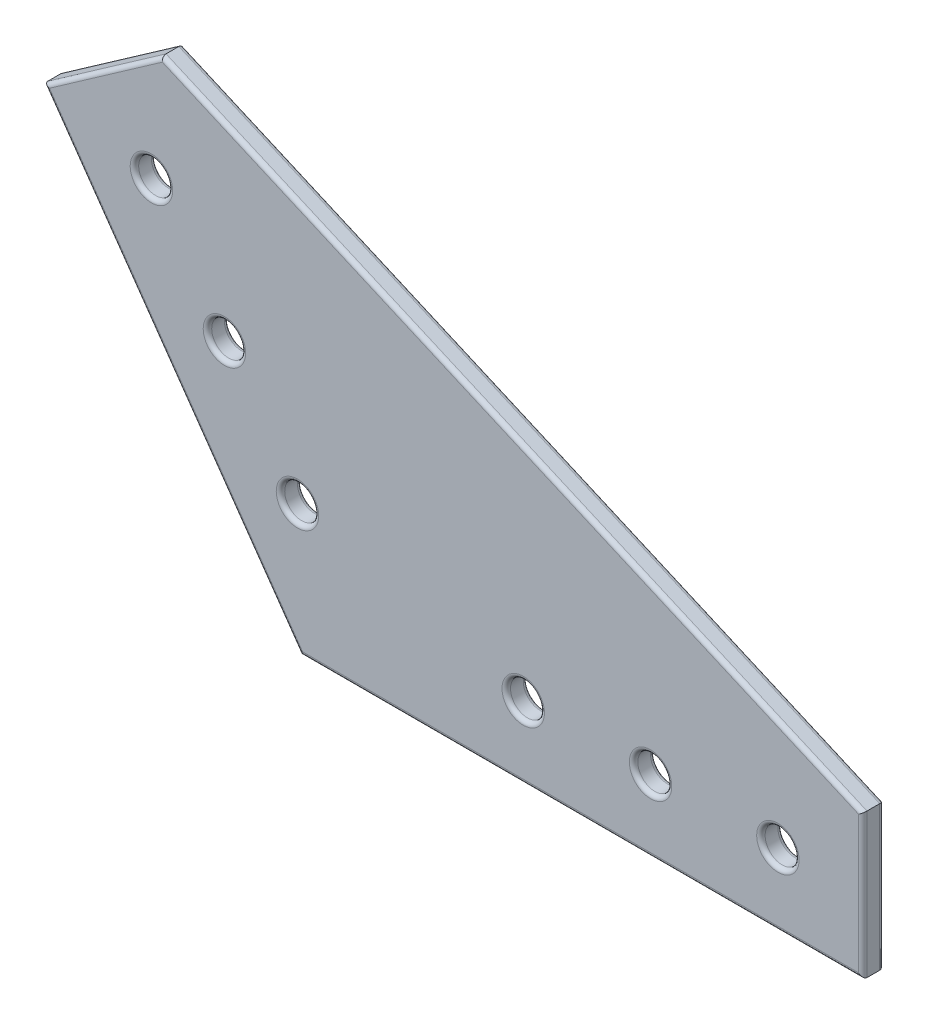
SolidWorks part; units mm, degrees
ref_plane "Front Plane" through (0, 0, 0) normal (0, 0, 1) x (1, 0, 0)
ref_plane "Top Plane" through (0, 0, 0) normal (0, 1, 0) x (1, 0, 0)
ref_plane "Right Plane" through (0, 0, 0) normal (1, 0, 0) x (0, 0, -1)
sketch "Sketch1" plane through (0, 0, 0) normal (0, 0, 1) x (1, 0, 0)
  line L0 (-141.463, 22.5991) -> (-113.6118, 42.1007)
  line L1 (-113.6118, 42.1007) -> (51.5493, -29.8214)
  line L2 (51.5493, -29.8214) -> (51.5493, -63.8214)
  line L3 (51.5493, -63.8214) -> (-80.9507, -63.8214)
  line L4 (-80.9507, -63.8214) -> (-141.463, 22.5991)
  dimension "D1" = 132.5
  dimension "D2" = 34
  dimension "D3" = 105.5
  dimension "D4" = 80.9507
  dimension "D5" = 63.8214
  dimension "D6" = 90
  dimension "D7" = 125
  dimension "D8" = 34
extrude "Boss-Extrude1" add sketch "Sketch1" along normal blind 5
sketch "Sketch2" plane through (0, 0, 5) normal (0, 0, 1) x (1, 0, 0)
  line L0 (-113.6118, 42.1007) -> (-39.4443, -63.8214) construction
  line L1 (-80.9507, -63.8214) -> (51.5493, -63.8214) construction
  line L2 (-141.463, 22.5991) -> (-80.9507, -63.8214) construction
  line L3 (51.5493, -29.8214) -> (-104.7577, -29.8214) construction
  line L4 (-127.5374, 32.3499) -> (-60.1975, -63.8214) construction
  line L5 (-113.6118, 42.1007) -> (-141.463, 22.5991) construction
  line L6 (51.5493, -46.8214) -> (-92.8542, -46.8214) construction
  line L7 (51.5493, -63.8214) -> (51.5493, -29.8214) construction
  line L8 (21.5493, -46.8214) -> (-122.8542, -46.8214) construction
  line L9 (-8.4507, -46.8214) -> (-152.8542, -46.8214) construction
  line L10 (-38.4507, -46.8214) -> (-182.8542, -46.8214) construction
  circle A0 centre (-116.0659, 15.9669) radius 4
  circle A1 centre (31.5493, -46.8214) radius 4
  circle A2 centre (-98.8586, -8.6077) radius 4
  circle A3 centre (-81.6513, -33.1822) radius 4
  circle A4 centre (1.5493, -46.8214) radius 4
  circle A5 centre (-28.4507, -46.8214) radius 4
  circle A7 centre (-58.4507, -46.8214) radius 4 [skipped]
  dimension "D1" = 8
  dimension "D2" = 8
  dimension "D4" = 20
  dimension "D5" = 30
  dimension "D7" = 20
  dimension "D8" = 30
  dimension "D3" = 3
  dimension "D6" = 4
extrude "Cut-Extrude1" cut sketch "Sketch2" against normal through all
fillet "Fillet2" radius 1 22 edges at (-127.5374, 32.3499, 0) (-111.2068, -20.6112, 0) (-14.7007, -63.8214, 0) (51.5493, -46.8214, 0) (-31.0312, 6.1396, 0) (5.5493, -46.8214, 0) (-77.6513, -33.1822, 0) (-94.8586, -8.6077, 0) (-112.0659, 15.9669, 0) (-24.4507, -46.8214, 0) (35.5493, -46.8214, 0) (-14.7007, -63.8214, 5) (-111.2068, -20.6112, 5) (-127.5374, 32.3499, 5) (-31.0312, 6.1396, 5) (51.5493, -46.8214, 5) (5.5493, -46.8214, 5) (-77.6513, -33.1822, 5) (-94.8586, -8.6077, 5) (-112.0659, 15.9669, 5) (-24.4507, -46.8214, 5) (35.5493, -46.8214, 5)
